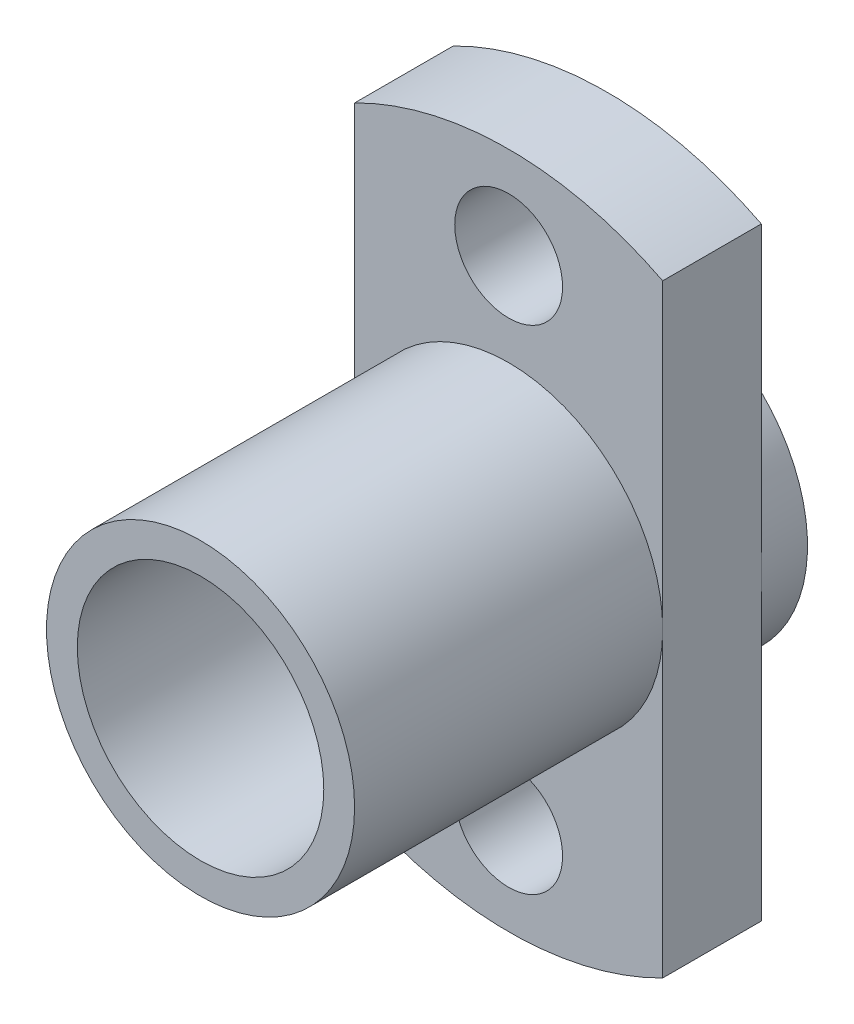
SolidWorks part; units mm, degrees
ref_plane "前视基准面" through (0, 0, 0) normal (0, 0, 1) x (1, 0, 0)
ref_plane "上视基准面" through (0, 0, 0) normal (0, 1, 0) x (1, 0, 0)
ref_plane "右视基准面" through (0, 0, 0) normal (1, 0, 0) x (0, 0, -1)
sketch "草图1" plane through (0, 0, 0) normal (0, 0, 1) x (1, 0, 0)
  circle A1 centre (0, 0) radius 11
  dimension "D1" = 22
extrude "凸台-拉伸1" add sketch "草图1" along normal blind 3.2 contours A1
sketch "草图2" plane through (0, 0, 3.2) normal (0, 0, 1) x (1, 0, 0)
  circle A0 centre (0, 0) radius 5
  dimension "D1" = 10
extrude "凸台-拉伸2" add sketch "草图2" along normal blind 10
sketch "草图3" plane through (0, 0, 13.2) normal (0, 0, 1) x (1, 0, 0)
  circle A0 centre (0, 0) radius 4
  dimension "D1" = 8
extrude "切除-拉伸1" cut sketch "草图3" along direction (0, 0, 1) on the side against the normal blind 15
sketch "草图4" plane through (0, 0, 0) normal (0, 0, -1) x (-1, 0, 0)
  circle A0 centre (0, 8) radius 1.75
  circle A1 centre (0, -8) radius 1.75
  point P12 (0, 0)
  dimension "D2" = 3.5
  dimension "D1" = 8
  dimension "D3" = 2
extrude "切除-拉伸2" cut sketch "草图4" against normal blind 7
sketch "草图6" plane through (0, 0, 3.2) normal (0, 0, 1) x (1, 0, 0)
  line L0 (0, 0) -> (0, 11) construction
  line L1 (0, 0) -> (-11, 0) construction
  line L2 (-5, 0) -> (-5, 10.3348)
  line L3 (-5, 10.3348) -> (-11, 10.3348)
  line L4 (-11, 10.3348) -> (-11, -9.8122)
  line L5 (-11, -9.8122) -> (-5, -9.8122)
  line L6 (-5, -9.8122) -> (-5, 0)
  line L7 (11, -9.8122) -> (5, -9.8122)
  line L8 (11, 10.3348) -> (11, -9.8122)
  line L9 (5, 10.3348) -> (11, 10.3348)
  line L10 (5, 0) -> (5, 10.3348)
  line L11 (5, -9.8122) -> (5, 0)
  circle A0 centre (0, 0) radius 11 construction
  dimension "D1" = 5
extrude "切除-拉伸4" cut sketch "草图6" against normal through all
sketch "草图7" plane through (0, 0, 0) normal (0, 0, -1) x (-1, 0, 0)
  circle A0 centre (0, 0) radius 5
  circle A1 centre (0, 0) radius 4 construction
  circle A2 centre (0, 0) radius 4
extrude "凸台-拉伸3" add sketch "草图7" along normal blind 1.5
